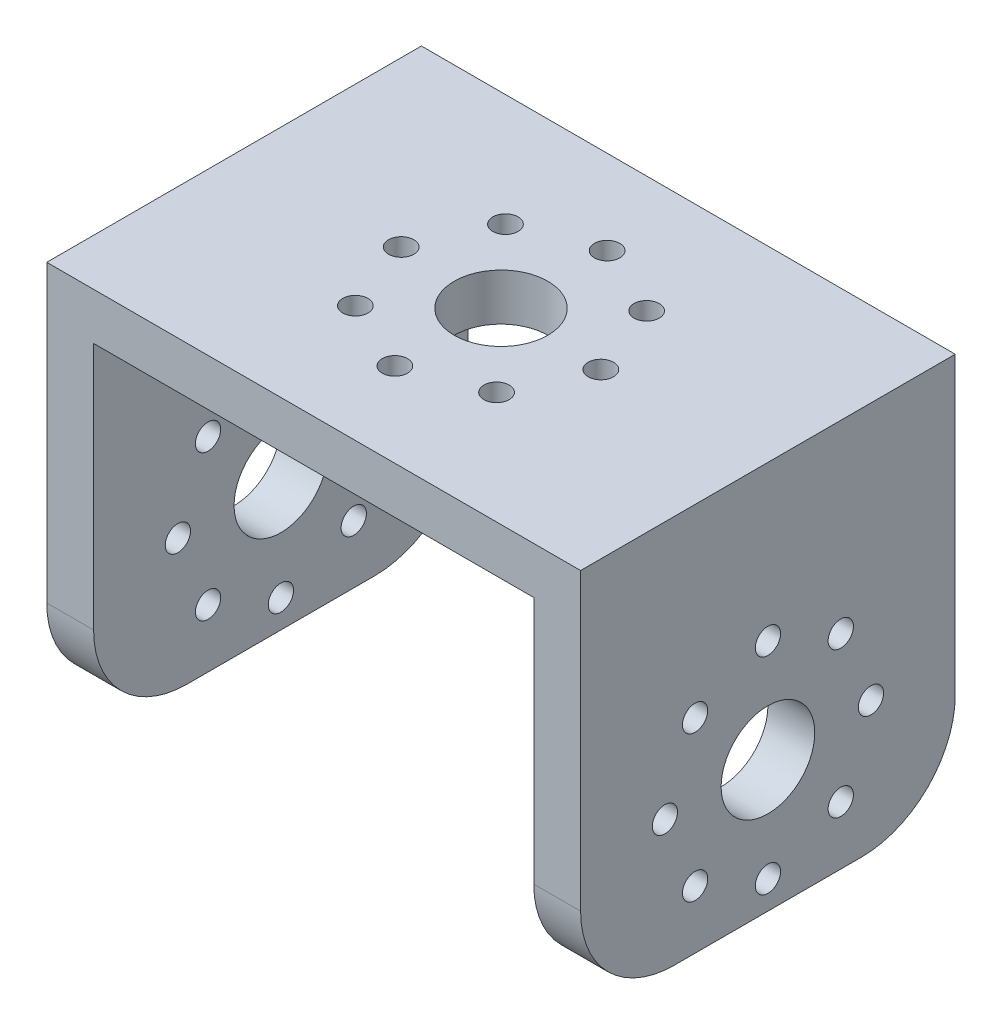
SolidWorks part; units mm, degrees
material "Aluminium 1050"
ref_plane "Front Plane" through (0, 0, 0) normal (0, 0, 1) x (1, 0, 0)
ref_plane "Top Plane" through (0, 0, 0) normal (0, 1, 0) x (1, 0, 0)
ref_plane "Right Plane" through (0, 0, 0) normal (1, 0, 0) x (0, 0, -1)
sketch "Sketch4" plane through (0, 0, 0) normal (0, 1, 0) x (1, 0, 0)
  line L0 (0, 0) -> (26.5, 0) construction
  line L1 (0, -20) -> (26.5, -20)
  line L2 (0, 20) -> (26.5, 20)
  line L3 (0, 29.6598) -> (0, -33.0341) construction
  line L4 (0, -20) -> (-26.5, -20)
  line L5 (0, 20) -> (-26.5, 20)
  line L6 (-26.5, 20) -> (-26.5, -20)
  line L7 (26.5, 20) -> (26.5, -20)
  circle A0 centre (0, 0) radius 14 construction
  circle A1 centre (0, 0) radius 5
  circle A2 centre (8.0122, 7.5369) radius 1.35
  circle A3 centre (10.9949, -0.3361) radius 1.35
  circle A4 centre (0.3361, 10.9949) radius 1.35
  circle A5 centre (-7.5369, 8.0122) radius 1.35
  circle A6 centre (-10.9949, 0.3361) radius 1.35
  circle A7 centre (-8.0122, -7.5369) radius 1.35
  circle A8 centre (-0.3361, -10.9949) radius 1.35
  circle A9 centre (7.5369, -8.0122) radius 1.35
  dimension "D1" = 28
  dimension "D5" = 10
  dimension "D6" = 2.7
  dimension "D7" = 2.7
  dimension "D8" = 2.7
  dimension "D9" = 2.7
  dimension "D10" = 2.7
  dimension "D11" = 2.7
  dimension "D12" = 2.7
  dimension "D13" = 2.7
  dimension "D2" = 26.5
  dimension "D3" = 20
  dimension "D4" = 20
extrude "Boss-Extrude1" add sketch "Sketch4" along normal blind 3
sketch "Sketch5" plane through (0, 0, 0) normal (0, -1, 0) x (1, 0, 0)
  line L0 (-26.5, 20) -> (-26.5, -20)
  line L1 (-26.5, -20) -> (-23.5, -20)
  line L2 (26.5, -20) -> (-26.5, -20) construction
  line L3 (-23.5, -20) -> (-23.5, 20)
  line L4 (-26.5, 20) -> (26.5, 20) construction
  line L5 (-23.5, 20) -> (-26.5, 20)
  line L6 (0, 20) -> (0, -20) construction
  line L7 (23.5, 20) -> (26.5, 20)
  line L8 (23.5, -20) -> (23.5, 20)
  line L9 (26.5, -20) -> (23.5, -20)
  line L10 (26.5, 20) -> (26.5, -20)
  dimension "D1" = 3
extrude "Boss-Extrude2" add sketch "Sketch5" along normal blind 60
sketch "Sketch7" plane through (26.5, 0, 0) normal (1, 0, 0) x (0, 0, -1)
  line L0 (-20, 0) -> (20, 0)
  line L1 (-20, -15) -> (20, -15) construction
  line L2 (-20, -22.5) -> (20, -22.5) construction
  line L3 (-10, -36.5) -> (10, -36.5)
  line L4 (-20, -26.5) -> (-20, 0)
  line L5 (20, -26.5) -> (20, 0)
  line L6 (-20, -36.5) -> (20, -36.5) construction
  line L7 (-20, -26.5) -> (-20, -60)
  line L8 (-20, -60) -> (20, -60)
  line L9 (20, -60) -> (20, -26.5)
  circle A0 centre (0, -22.5) radius 5
  arc A1 (-10, -36.5) -> (-20, -26.5) centre (-10, -26.5) cw
  arc A2 (10, -36.5) -> (20, -26.5) centre (10, -26.5) ccw
  circle A11 centre (0, -22.5) radius 11 construction
  circle A12 centre (0, -11.5) radius 1.35
  circle A13 centre (7.7782, -14.7218) radius 1.35
  circle A14 centre (11, -22.5) radius 1.35
  circle A15 centre (7.7782, -30.2782) radius 1.35
  circle A16 centre (0, -33.5) radius 1.35
  circle A17 centre (-7.7782, -30.2782) radius 1.35
  circle A18 centre (-11, -22.5) radius 1.35
  circle A19 centre (-7.7782, -14.7218) radius 1.35
  point P50 (0, -22.5)
  dimension "D3" = 10
  dimension "D5" = 10
  dimension "D6" = 22
  dimension "D7" = 2.7
  dimension "D8" = 8
  dimension "D1" = 15
  dimension "D2" = 7.5
  dimension "D4" = 14
extrude "Cut-Extrude1" cut sketch "Sketch7" against normal through all both and the other way through all
sketch "Sketch8" plane through (0, 3, 0) normal (0, 1, 0) x (1, 0, 0)
  line L0 (-26.5, 20) -> (26.5, 20)
  line L1 (26.5, 20) -> (28.5, 20)
  line L2 (28.5, 20) -> (28.5, -20)
  line L3 (28.5, -20) -> (26.5, -20)
  line L4 (26.5, -20) -> (-26.5, -20)
  line L5 (-26.5, -20) -> (-28.5, -20)
  line L6 (-28.5, -20) -> (-28.5, 20)
  line L7 (-28.5, 20) -> (-26.5, 20)
  circle A0 centre (0, 0) radius 5
  circle A1 centre (8.0122, 7.5369) radius 1.35
  circle A2 centre (0.3361, 10.9949) radius 1.35
  circle A3 centre (-7.5369, 8.0122) radius 1.35
  circle A4 centre (-10.9949, 0.3361) radius 1.35
  circle A5 centre (-8.0122, -7.5369) radius 1.35
  circle A6 centre (-0.3361, -10.9949) radius 1.35
  circle A7 centre (7.5369, -8.0122) radius 1.35
  circle A8 centre (10.9949, -0.3361) radius 1.35
  dimension "D1" = 2
  dimension "D2" = 2
extrude "Boss-Extrude3" add sketch "Sketch8" along normal blind 2
sketch "Sketch9" plane through (0, 0, 0) normal (1, 0, 0) x (0, 0, -1)
  line L0 (20, 3) -> (20, -26.5)
  line L1 (20, 3) -> (-20, 3)
  line L2 (-20, 3) -> (-20, -26.5)
  line L3 (-10, -36.5) -> (10, -36.5)
  circle A0 centre (11, -22.5) radius 1.35
  circle A1 centre (7.7782, -14.7218) radius 1.35
  circle A2 centre (0, -11.5) radius 1.35
  circle A3 centre (0, -22.5) radius 5
  circle A4 centre (7.7782, -30.2782) radius 1.35
  circle A5 centre (0, -33.5) radius 1.35
  circle A6 centre (-7.7782, -30.2782) radius 1.35
  circle A7 centre (-11, -22.5) radius 1.35
  circle A8 centre (-7.7782, -14.7218) radius 1.35
  arc A9 (20, -26.5) -> (10, -36.5) centre (10, -26.5) cw
  arc A10 (-10, -36.5) -> (-20, -26.5) centre (-10, -26.5) cw
sketch "Sketch10" plane through (-28.5, 0, 0) normal (-1, 0, 0) x (0, 0, 1)
  line L0 (-20, 3) -> (-20, -26.5)
  line L1 (-20, 3) -> (20, 3)
  line L2 (20, 3) -> (20, -26.5)
  line L3 (10, -36.5) -> (-10, -36.5)
  arc A0 (-20, -26.5) -> (-10, -36.5) centre (-10, -26.5) ccw
  arc A1 (10, -36.5) -> (20, -26.5) centre (10, -26.5) ccw
  circle A2 centre (0, -22.5) radius 5
  circle A3 centre (-7.7782, -14.7218) radius 1.35
  circle A4 centre (-11, -22.5) radius 1.35
  circle A5 centre (-7.7782, -30.2782) radius 1.35
  circle A6 centre (0, -33.5) radius 1.35
  circle A7 centre (7.7782, -30.2782) radius 1.35
  circle A8 centre (11, -22.5) radius 1.35
  circle A9 centre (7.7782, -14.7218) radius 1.35
  circle A10 centre (0, -11.5) radius 1.35
extrude "Boss-Extrude4" add sketch "Sketch10" against normal blind 5
extrude "Boss-Extrude5" add sketch "Sketch10" along normal blind 5 from surface at -57 starting at face at (28.5, 4, 0)
